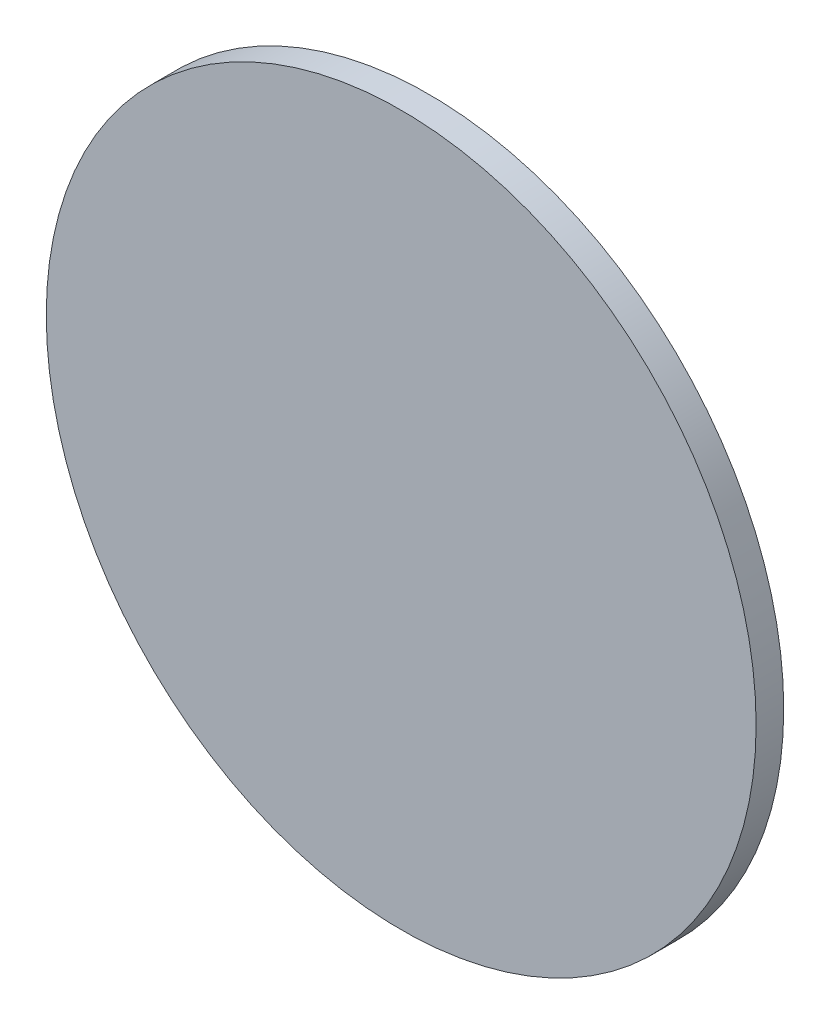
SolidWorks part; units mm, degrees
ref_plane "Alzado" through (0, 0, 0) normal (0, 0, 1) x (1, 0, 0)
ref_plane "Planta" through (0, 0, 0) normal (0, 1, 0) x (1, 0, 0)
ref_plane "Vista lateral" through (0, 0, 0) normal (1, 0, 0) x (0, 0, -1)
sketch "Croquis1" plane through (0, 0, 0) normal (0, 0, 1) x (1, 0, 0)
  circle A0 centre (0, 0) radius 45
  dimension "D1" = 90
extrude "Disk" add sketch "Croquis1" along normal blind 3.5
sketch "Croquis6" plane through (0, 0, 3.5) normal (0, 0, 1) x (1, 0, 0)
  line L6 (0, 0) -> (0, 45) construction
  circle A17 centre (0, 0) radius 45 construction
  circle A18 centre (0, 38) radius 3
  circle A20 centre (32.909, -19) radius 3
  circle A21 centre (-32.909, -19) radius 3
  arc A22 (0, 0) -> (-28.0484, -3.2701) centre (-14.8958, 5.8408) cw
  arc A24 (-28.0484, -3.2701) -> (0, 0) centre (-14.8958, 5.8408) ccw
  arc A25 (0, 38) -> (-28.0484, -3.2701) centre (-6.0667, 11.9568) ccw
  arc A26 (32.909, -19) -> (11.1922, 25.9257) centre (13.3883, -0.7245) ccw
  arc A27 (0, 0) -> (11.1922, 25.9257) centre (12.5062, 9.9797) cw
  arc A28 (-32.909, -19) -> (16.8562, -22.6556) centre (-7.3215, -11.2323) ccw
  arc A29 (0, 0) -> (16.8562, -22.6556) centre (2.3896, -15.8206) cw
  arc A30 (0.6806, 40.9218) -> (-30.5145, -4.9784) centre (-6.0667, 11.9568) ccw
  arc A31 (2.3449, 1.8712) -> (11.4386, 22.9358) centre (12.5062, 9.9797) cw
  arc A33 (30.7189, -16.9497) -> (11.4386, 22.9358) centre (13.3883, -0.7245) ccw
  arc A34 (-2.793, 1.0952) -> (-25.5823, -1.5618) centre (-14.8958, 5.8408) cw
  arc A35 (0.448, -2.9664) -> (14.1437, -21.374) centre (2.3896, -15.8206) cw
  arc A36 (-30.0383, -18.1286) -> (14.1437, -21.374) centre (-7.3215, -11.2323) ccw
  arc A37 (-0.6806, 35.0782) -> (-25.5823, -1.5618) centre (-6.0667, 11.9568) ccw
  arc A38 (-2.3449, -1.8712) -> (10.9458, 28.9155) centre (12.5062, 9.9797) cw
  arc A39 (35.099, -21.0503) -> (10.9458, 28.9155) centre (13.3883, -0.7245) ccw
  arc A40 (2.793, -1.0952) -> (-30.5145, -4.9784) centre (-14.8958, 5.8408) cw
  arc A41 (-0.448, 2.9664) -> (19.5687, -23.9371) centre (2.3896, -15.8206) cw
  arc A42 (-35.7796, -19.8714) -> (19.5687, -23.9371) centre (-7.3215, -11.2323) ccw
  circle A43 centre (0, 0) radius 4
  point P14 (0, 0)
  point P27 (0, 0)
  dimension "D1" = 6
  dimension "D3" = 16
  dimension "D5" = 3
  dimension "D2" = 38
  dimension "D6" = 3
  dimension "D4" = 3
